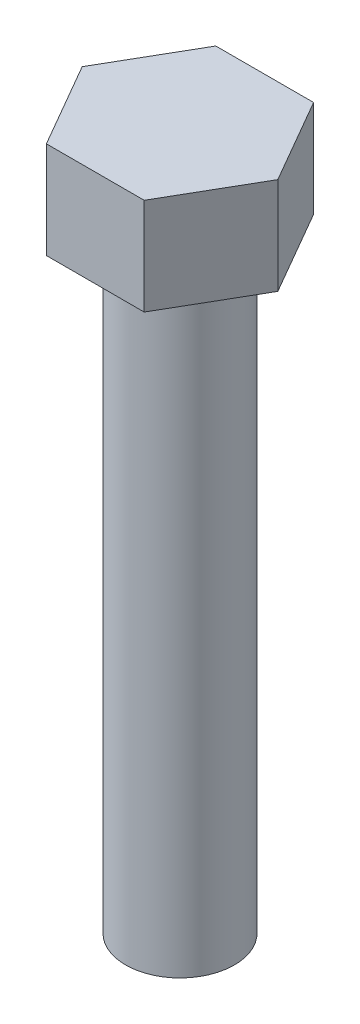
SolidWorks part; units mm, degrees
ref_plane "Front Plane" through (0, 0, 0) normal (0, 0, 1) x (1, 0, 0)
ref_plane "Top Plane" through (0, 0, 0) normal (0, 1, 0) x (1, 0, 0)
ref_plane "Right Plane" through (0, 0, 0) normal (1, 0, 0) x (0, 0, -1)
sketch "Sketch2" plane through (0, 0, 0) normal (0, 0, 1) x (1, 0, 0)
  line L0 (0, 0) -> (0, 25)
  line L1 (0, 25) -> (2.25, 25)
  line L2 (2.25, 25) -> (2.25, 0)
  line L3 (2.25, 0) -> (0, 0)
  dimension "D1" = 25
  dimension "D2" = 2.25
revolve "Revolve1" add sketch "Sketch2" angle 360 about L0
sketch "Sketch3" plane through (0, 25, 0) normal (0, 1, 0) x (1, 0, 0)
  line L1 (4.0415, 0) -> (2.0207, 3.5)
  line L2 (2.0207, 3.5) -> (-2.0207, 3.5)
  line L3 (-2.0207, 3.5) -> (-4.0415, 0)
  line L4 (-4.0415, 0) -> (-2.0207, -3.5)
  line L5 (-2.0207, -3.5) -> (2.0207, -3.5)
  line L6 (2.0207, -3.5) -> (4.0415, 0)
  circle A0 centre (0, 0) radius 3.5 construction
  dimension "D1" = 7
extrude "Boss-Extrude1" add sketch "Sketch3" along normal blind 4
